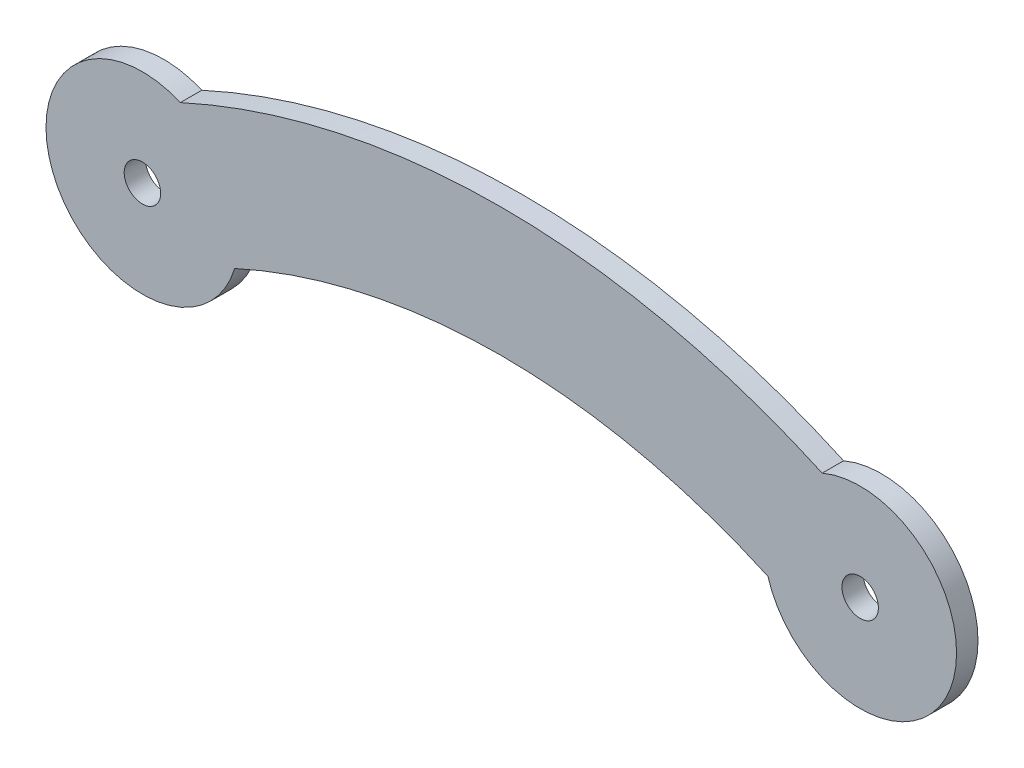
SolidWorks part; units mm, degrees
material "Латунь"
ref_plane "Front" through (0, 0, 0) normal (0, 0, 1) x (1, 0, 0)
ref_plane "Top" through (0, 0, 0) normal (0, 1, 0) x (1, 0, 0)
ref_plane "Right" through (0, 0, 0) normal (1, 0, 0) x (0, 0, -1)
sketch "Эскиз1" plane through (0, 0, 0) normal (0, 0, 1) x (1, 0, 0)
  line L0 (91.0915, -74.9278) -> (299.1892, 26.119) construction
  line L1 (-4.5, 9.3446) -> (-4.5, -4.5) construction
  line L2 (1.7719, 4.1365) -> (4.3077, -1.3015) construction
  line L3 (0, 0) -> (16.75, 7.8107) construction
  line L4 (29.1923, -1.3015) -> (31.7281, 4.1365) construction
  line L5 (16.75, 7.8107) -> (33.5, 0) construction
  line L6 (16.75, 7.8107) -> (16.75, -28.5997) construction
  line L7 (38, 6.2965) -> (38, -4.5) construction
  line L8 (0, 0) -> (33.5, 0) construction
  line L9 (-4.5, -4.5) -> (38, -4.5) construction
  circle A0 centre (0, 0) radius 0.85
  arc A2 (4.3077, -1.3015) -> (1.7719, 4.1365) centre (0, 0) cw
  arc A3 (4.3077, -1.3015) -> (29.1923, -1.3015) centre (16.75, -28.5997) cw
  arc A4 (1.7719, 4.1365) -> (31.7281, 4.1365) centre (16.75, -28.5997) cw
  arc A5 (29.1923, -1.3015) -> (31.7281, 4.1365) centre (33.5, 0) ccw
  circle A6 centre (33.5, 0) radius 0.85
  point P0 (16.75, 1.4003)
  point P13 (30.4602, 1.4175)
  point P14 (3.0398, 1.4175)
  point P20 (16.75, 7.4003)
  dimension "D1" = 1.7
  dimension "D2" = 4.5
  dimension "D3" = 30
  dimension "D4" = 6
  dimension "D7" = 11.9003
  dimension "D5" = 130
  dimension "D6" = 42.5
extrude "Бобышка-Вытянуть1" add sketch "Эскиз1" along normal blind 1
